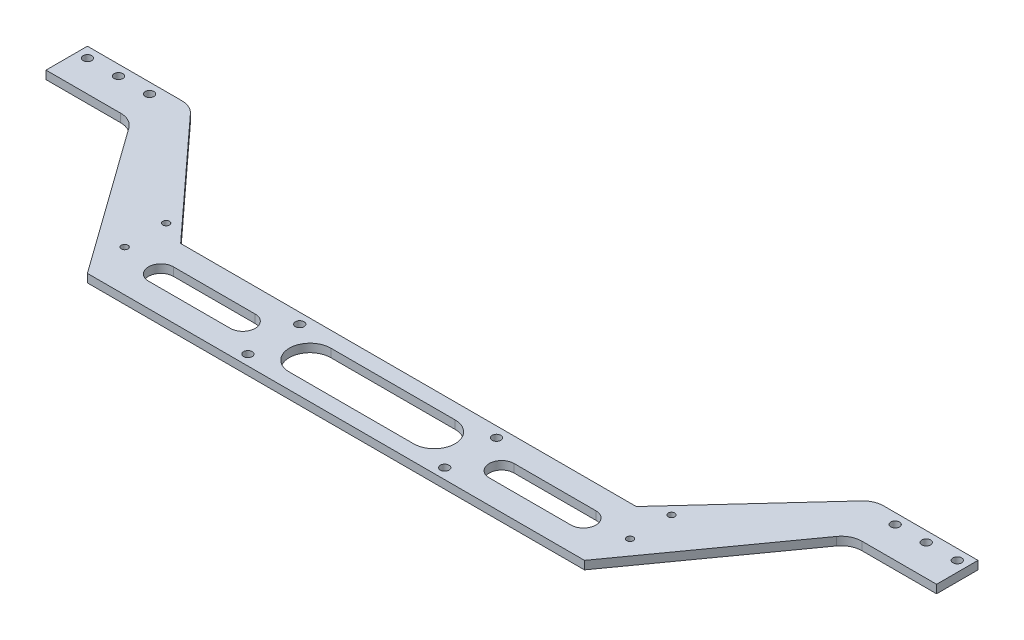
SolidWorks part; units mm, degrees
material "Thornel Mat VMA"
ref_plane "前视基准面" through (0, 0, 0) normal (0, 0, 1) x (1, 0, 0)
ref_plane "上视基准面" through (0, 0, 0) normal (0, 1, 0) x (1, 0, 0)
ref_plane "右视基准面" through (0, 0, 0) normal (1, 0, 0) x (0, 0, -1)
sketch "草图2" plane through (0, 0, 0) normal (0, 1, 0) x (1, 0, 0)
  line L1 (0, 0) -> (95, 0) construction
  line L2 (0, 0) -> (0, 25) construction
  line L3 (0, 25) -> (95, 25) construction
  line L4 (95, 0) -> (95, 25) construction
  line L5 (-72.5, -5) -> (167.5, -5)
  line L6 (-62.5, 30) -> (157.5, 30)
  line L7 (47.5, 25) -> (47.5, 0) construction
  line L9 (-72.5, -5) -> (-126.298, 70)
  line L10 (-126.298, 70) -> (-167.5, 70)
  line L11 (-167.5, 70) -> (-167.5, 90)
  line L12 (-167.5, 90) -> (-117.5, 90)
  line L13 (-117.5, 90) -> (-62.5, 30)
  line L14 (167.5, -5) -> (221.298, 70)
  line L15 (221.298, 70) -> (262.5, 70)
  line L16 (262.5, 70) -> (262.5, 90)
  line L17 (262.5, 90) -> (212.5, 90)
  line L18 (212.5, 90) -> (157.5, 30)
  line L19 (-162.5, 85) -> (-132.5, 85) construction
  line L20 (257.5, 85) -> (227.5, 85) construction
  line L21 (77.5, 12.5) -> (17.5, 12.5) construction
  line L22 (77.5, 2.5) -> (17.5, 2.5)
  line L23 (77.5, 22.5) -> (17.5, 22.5)
  circle A0 centre (0, 0) radius 2.1
  circle A1 centre (95, 0) radius 2.1
  circle A2 centre (95, 25) radius 2.1
  circle A3 centre (0, 25) radius 2.1
  circle A4 centre (-162.5, 85) radius 2.1
  circle A5 centre (-147.5, 85) radius 2.1
  circle A6 centre (-132.5, 85) radius 2.1
  circle A7 centre (227.5, 85) radius 2.1
  circle A8 centre (242.5, 85) radius 2.1
  circle A9 centre (257.5, 85) radius 2.1
  arc A10 (77.5, 2.5) -> (77.5, 22.5) centre (77.5, 12.5) ccw
  arc A11 (17.5, 22.5) -> (17.5, 2.5) centre (17.5, 12.5) ccw
  point P37 (47.5, 12.5)
  dimension "D3" = 4.2
  dimension "D13" = 4.2
  dimension "D17" = 10
  dimension "D1" = 25
  dimension "D2" = 95
  dimension "D4" = 55
  dimension "D5" = 220
  dimension "D6" = 20
  dimension "D7" = 50
  dimension "D8" = 60
  dimension "D9" = 240
  dimension "D10" = 5
  dimension "D11" = 5
  dimension "D12" = 20
  dimension "D14" = 5
  dimension "D15" = 5
  dimension "D16" = 30
  dimension "D18" = 60
extrude "凸台-拉伸1" add sketch "草图2" along normal blind 4
sketch "草图3" plane through (0, 0, 0) normal (0, -1, 0) x (1, 0, 0)
  line L0 (169.5, -35) -> (169.5, -15) construction
  line L1 (-72.5, 5) -> (167.5, 5) construction
  line L2 (47.5, 5) -> (47.5, -30) construction
  line L3 (157.5, -30) -> (-62.5, -30) construction
  line L4 (-74.5, -35) -> (-74.5, -15) construction
  circle A0 centre (169.5, -35) radius 1.6
  circle A1 centre (169.5, -15) radius 1.6
  circle A2 centre (-74.5, -15) radius 1.6
  circle A3 centre (-74.5, -35) radius 1.6
  point P6 (47.5, 5)
  dimension "D1" = 3.2
  dimension "D2" = 20
  dimension "D3" = 20
  dimension "D4" = 122
extrude "切除-拉伸1" cut sketch "草图3" against normal blind 10
fillet "圆角1" radius 10 4 edges at (221.298, 2, -70) (212.5, 2, -90) (-126.298, 2, -70) (-117.5, 2, -90)
sketch "草图4" plane through (0, 4, 0) normal (0, 1, 0) x (1, 0, 0)
  line L0 (-54.5, 12.5) -> (-15, 12.5) construction
  line L1 (-54.5, 18.5) -> (-15, 18.5)
  line L2 (-54.5, 6.5) -> (-15, 6.5)
  line L3 (47.5, 30) -> (47.5, -5) construction
  line L4 (157.5, 30) -> (-62.5, 30) construction
  line L5 (-72.5, -5) -> (167.5, -5) construction
  line L6 (149.5, 12.5) -> (110, 12.5) construction
  line L7 (149.5, 18.5) -> (110, 18.5)
  line L8 (149.5, 6.5) -> (110, 6.5)
  arc A0 (-54.5, 18.5) -> (-54.5, 6.5) centre (-54.5, 12.5) ccw
  arc A1 (-15, 6.5) -> (-15, 18.5) centre (-15, 12.5) ccw
  circle A2 centre (-74.5, 15) radius 1.6 construction
  circle A3 centre (0, 25) radius 2.1 construction
  arc A4 (149.5, 18.5) -> (149.5, 6.5) centre (149.5, 12.5) cw
  arc A5 (110, 6.5) -> (110, 18.5) centre (110, 12.5) cw
  point P2 (-34.75, 12.5)
  point P13 (47.5, 12.5)
  point P20 (129.75, 12.5)
  dimension "D1" = 6
  dimension "D2" = 20
  dimension "D3" = 15
extrude "切除-拉伸2" cut sketch "草图4" against normal through all
